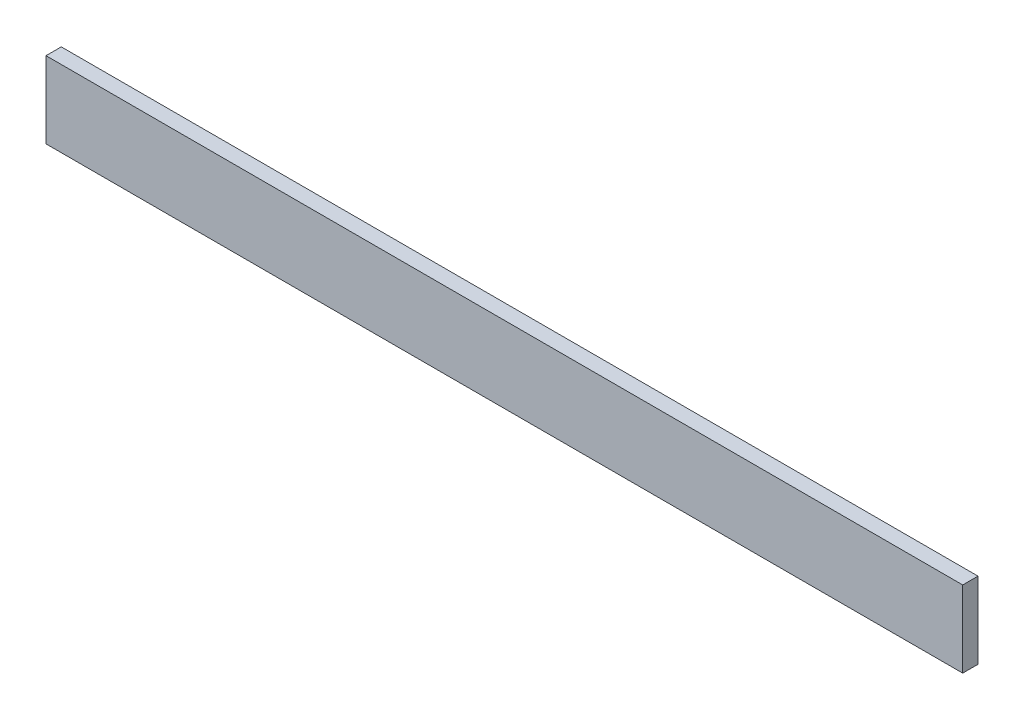
SolidWorks part; units mm, degrees
ref_plane "Front Plane" through (0, 0, 0) normal (0, 0, 1) x (1, 0, 0)
ref_plane "Top Plane" through (0, 0, 0) normal (0, 1, 0) x (1, 0, 0)
ref_plane "Right Plane" through (0, 0, 0) normal (1, 0, 0) x (0, 0, -1)
sketch "Esquisse1" plane through (0, 0, 0) normal (0, 0, 1) x (1, 0, 0)
  line L1 (0, 0) -> (-180, 0)
  line L2 (0, 0) -> (0, 15)
  line L3 (0, 15) -> (-180, 15)
  line L4 (-180, 0) -> (-180, 15)
  dimension "D1" = 15
  dimension "D2" = 180
extrude "Boss.-Extru.1" add sketch "Esquisse1" along normal blind 3
